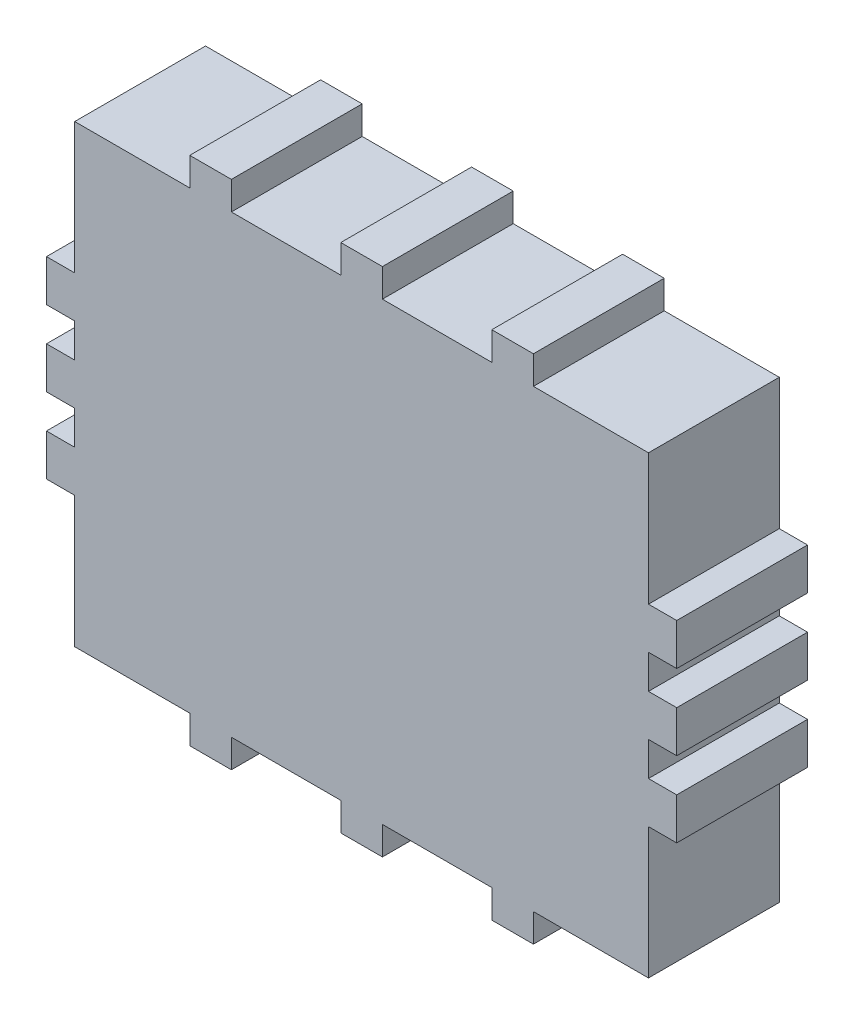
SolidWorks part; units mm, degrees
ref_plane "前视基准面" through (0, 0, 0) normal (0, 0, 1) x (1, 0, 0)
ref_plane "上视基准面" through (0, 0, 0) normal (0, 1, 0) x (1, 0, 0)
ref_plane "右视基准面" through (0, 0, 0) normal (1, 0, 0) x (0, 0, -1)
sketch "草图1" plane through (0, 0, 0) normal (0, 0, 1) x (1, 0, 0)
  line L0 (-2.89, -4.3) -> (-2.89, -3.825)
  line L1 (-2.89, -3.825) -> (-4.825, -3.825)
  line L2 (-4.825, -3.825) -> (-4.825, -1.62)
  line L3 (-4.825, -1.62) -> (-5.3, -1.62)
  line L4 (-5.3, -1.62) -> (-5.3, -0.92)
  line L5 (-5.3, -0.92) -> (-4.825, -0.92)
  line L6 (-4.825, -0.92) -> (-4.825, -0.35)
  line L7 (-4.825, -0.35) -> (-5.3, -0.35)
  line L8 (-5.3, -0.35) -> (-5.3, 0.35)
  line L9 (-5.3, 0.35) -> (-4.825, 0.35)
  line L10 (-4.825, 0.35) -> (-4.825, 0.92)
  line L11 (-4.825, 0.92) -> (-5.3, 0.92)
  line L12 (-5.3, 0.92) -> (-5.3, 1.62)
  line L13 (-5.3, 1.62) -> (-4.825, 1.62)
  line L14 (-4.825, 1.62) -> (-4.825, 3.825)
  line L15 (-4.825, 3.825) -> (-2.89, 3.825)
  line L16 (-2.89, 3.825) -> (-2.89, 4.3)
  line L17 (-2.89, 4.3) -> (-2.19, 4.3)
  line L18 (-2.19, 4.3) -> (-2.19, 3.825)
  line L19 (-2.19, 3.825) -> (-0.35, 3.825)
  line L20 (-0.35, 3.825) -> (-0.35, 4.3)
  line L21 (-0.35, 4.3) -> (0.35, 4.3)
  line L22 (0.35, 4.3) -> (0.35, 3.825)
  line L23 (0.35, 3.825) -> (2.19, 3.825)
  line L24 (2.19, 3.825) -> (2.19, 4.3)
  line L25 (2.19, 4.3) -> (2.89, 4.3)
  line L26 (2.89, 4.3) -> (2.89, 3.825)
  line L27 (2.89, 3.825) -> (4.825, 3.825)
  line L28 (4.825, 3.825) -> (4.825, 1.62)
  line L29 (4.825, 1.62) -> (5.3, 1.62)
  line L30 (5.3, 1.62) -> (5.3, 0.92)
  line L31 (5.3, 0.92) -> (4.825, 0.92)
  line L32 (4.825, 0.92) -> (4.825, 0.35)
  line L33 (4.825, 0.35) -> (5.3, 0.35)
  line L34 (5.3, 0.35) -> (5.3, -0.35)
  line L35 (5.3, -0.35) -> (4.825, -0.35)
  line L36 (4.825, -0.35) -> (4.825, -0.92)
  line L37 (4.825, -0.92) -> (5.3, -0.92)
  line L38 (5.3, -0.92) -> (5.3, -1.62)
  line L39 (5.3, -1.62) -> (4.825, -1.62)
  line L40 (4.825, -1.62) -> (4.825, -3.825)
  line L41 (4.825, -3.825) -> (2.89, -3.825)
  line L42 (2.89, -3.825) -> (2.89, -4.3)
  line L43 (2.89, -4.3) -> (2.19, -4.3)
  line L44 (2.19, -4.3) -> (2.19, -3.825)
  line L45 (2.19, -3.825) -> (0.35, -3.825)
  line L46 (0.35, -3.825) -> (0.35, -4.3)
  line L47 (0.35, -4.3) -> (-0.35, -4.3)
  line L48 (-0.35, -4.3) -> (-0.35, -3.825)
  line L49 (-0.35, -3.825) -> (-2.19, -3.825)
  line L50 (-2.19, -3.825) -> (-2.19, -4.3)
  line L51 (-2.19, -4.3) -> (-2.89, -4.3)
extrude "Component_Outline" add sketch "草图1" along normal blind 2.2 separate body
sketch3d "3D草图1"
  line L0 (0, 0, 0) -> (1, 0, 0)
  line L1 (0, 0, 0) -> (0, 1, 0)
  line L2 (0, 0, 0) -> (0, 0, 1)
  point P0 (0, 0, 0)
